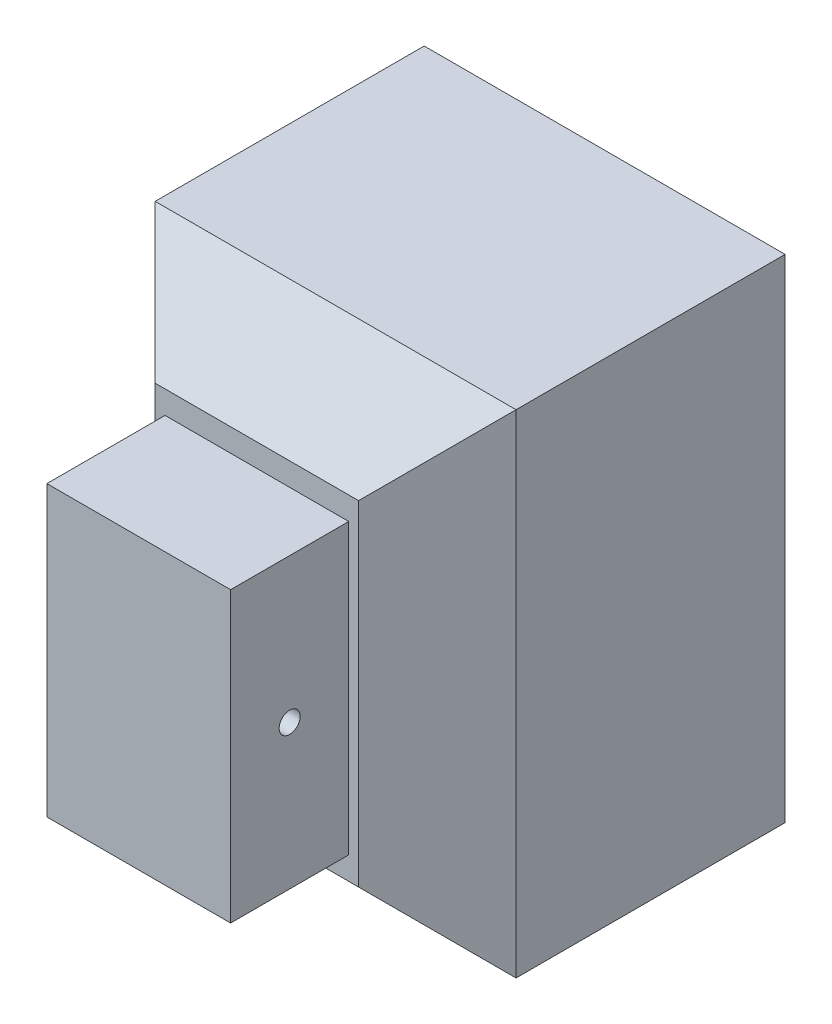
SolidWorks part; units mm, degrees
ref_plane "Front Plane" through (0, 0, 0) normal (1, 0, 0) x (0, 1, 0)
ref_plane "Top Plane" through (0, 0, 0) normal (0, 0, 1) x (0, 1, 0)
ref_plane "Right Plane" through (0, 0, 0) normal (0, 1, 0) x (-1, 0, 0)
sketch "Sketch1" plane through (0, 0, 0) normal (1, 0, 0) x (0, 1, 0)
  line L1 (-32.1033, 29.2989) -> (42.8967, 29.2989)
  line L2 (-32.1033, 29.2989) -> (-32.1033, -35.7011)
  line L3 (-32.1033, -35.7011) -> (42.8967, -35.7011)
  line L4 (42.8967, 29.2989) -> (42.8967, -35.7011)
  dimension "D1" = 75
  dimension "D2" = 65
extrude "Boss-Extrude1" add sketch "Sketch1" along normal blind 55
sketch "Sketch2" plane through (0, 0, 29.2989) normal (0, 0, 1) x (1, 0, 0)
  line L0 (0, 42.8967) -> (55, -32.1033) construction
  line L1 (13.5, 27.3967) -> (41.5, 27.3967)
  line L2 (13.5, 27.3967) -> (13.5, -16.6033)
  line L3 (13.5, -16.6033) -> (41.5, -16.6033)
  line L4 (41.5, 27.3967) -> (41.5, -16.6033)
  line L5 (27.5, 42.8967) -> (27.5, -32.1033) construction
  line L6 (55, 42.8967) -> (0, 42.8967) construction
  line L7 (55, -32.1033) -> (0, -32.1033) construction
  line L8 (13.5, 5.3967) -> (41.5, 5.3967) construction
  point P16 (27.5, 5.3967)
  point P17 (27.5, 5.3967)
  dimension "D1" = 44
  dimension "D2" = 28
extrude "Boss-Extrude2" add sketch "Sketch2" along normal blind 18
chamfer "Chamfer1" distance 12 angle 45 8 edges at (27.5, -32.1033, 29.2989) (0, 5.3967, 29.2989) (27.5, 42.8967, 29.2989) (55, 5.3967, 29.2989) (27.5, -32.1033, -35.7011) (0, 5.3967, -35.7011) (27.5, 42.8967, -35.7011) (55, 5.3967, -35.7011)
sketch "Sketch3" plane through (41.5, 0, 0) normal (1, 0, 0) x (0, 1, 0)
  circle A0 centre (5.3967, 38.2989) radius 1.6
  dimension "D1" = 3.2
extrude "Cut-Extrude1" cut sketch "Sketch3" against normal through all both and the other way through all
